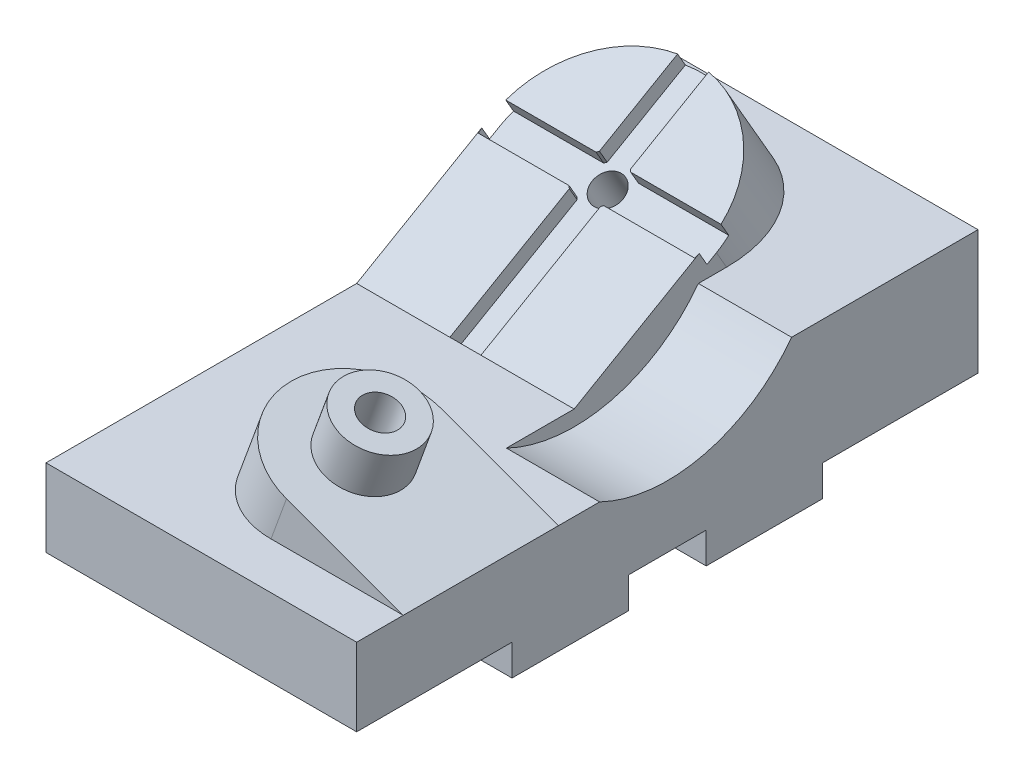
SolidWorks part; units mm, degrees
material "6061 Alloy"
ref_plane "Front Plane" through (0, 0, 0) normal (0, 0, 1) x (1, 0, 0)
ref_plane "Top Plane" through (0, 0, 0) normal (0, 1, 0) x (1, 0, 0)
ref_plane "Right Plane" through (0, 0, 0) normal (1, 0, 0) x (0, 0, -1)
sketch "Sketch1" plane through (0, 0, 0) normal (0, 1, 0) x (1, 0, 0)
  line L1 (0, 0) -> (100, 0)
  line L2 (0, 0) -> (0, -200)
  line L3 (0, -200) -> (100, -200)
  line L4 (100, 0) -> (100, -200)
  dimension "D1" = 100
  dimension "D2" = 200
extrude "Boss-Extrude1" add sketch "Sketch1" along normal blind 25
ref_plane "Plane1" through (19.7326, 54.2149, 0) normal (0.342, 0.9397, 0) x (0, 0, -1)
sketch "Sketch3" plane through (19.7326, 54.2149, 0) normal (0.342, 0.9397, 0) x (0, 0, -1)
  line L0 (-200, -85.4188) -> (0, -85.4188) construction
  line L1 (-185, -85.4188) -> (-135, -85.4188)
  line L2 (-185, -85.4188) -> (-185, -45.4188)
  line L4 (-135, -85.4188) -> (-135, -45.4188)
  arc A0 (-135, -45.4188) -> (-185, -45.4188) centre (-160, -45.4188) ccw
  dimension "D1" = 15
  dimension "D2" = 50
  dimension "D3" = 40
extrude "Boss-Extrude3" add sketch "Sketch3" against normal up to surface (26.6044 mm away)
sketch "Sketch4" plane through (19.7326, 54.2149, 0) normal (0.342, 0.9397, 0) x (0.9397, -0.342, 0)
  circle A0 centre (45.4188, -160) radius 12.5
  dimension "D1" = 25
extrude "Boss-Extrude4" add sketch "Sketch4" along normal blind 15
sketch "Sketch5" plane through (24.8629, 68.3103, 0) normal (0.342, 0.9397, 0) x (0.9397, -0.342, 0)
  circle A0 centre (45.4188, -160) radius 6
  dimension "D1" = 12
extrude "Cut-Extrude1" cut sketch "Sketch5" against normal through all
sketch "Sketch6" plane through (0, 0, 0) normal (0, -1, 0) x (1, 0, 0)
  line L0 (100, 200) -> (100, 0) construction
  line L1 (100, 150) -> (0, 150)
  line L2 (100, 150) -> (100, 112.5)
  line L3 (100, 112.5) -> (0, 112.5)
  line L4 (0, 150) -> (0, 112.5)
  line L5 (0, 0) -> (0, 200) construction
  line L6 (0, 200) -> (100, 200) construction
  dimension "D1" = 50
  dimension "D2" = 37.5
extrude "Boss-Extrude5" add sketch "Sketch6" along normal blind 10
sketch "Sketch7" plane through (0, 0, 0) normal (0, -1, 0) x (1, 0, 0)
  line L0 (100, 112.5) -> (100, 0) construction
  line L1 (100, 87.5) -> (0, 87.5)
  line L2 (100, 87.5) -> (100, 50)
  line L3 (100, 50) -> (0, 50)
  line L4 (0, 87.5) -> (0, 50)
  line L5 (0, 0) -> (0, 112.5) construction
  line L6 (0, 112.5) -> (100, 112.5) construction
  line L7 (100, 150) -> (0, 150) construction
  dimension "D1" = 25
  dimension "D2" = 100
extrude "Boss-Extrude6" add sketch "Sketch7" along normal blind 10
sketch "Sketch8" plane through (0, 25, 0) normal (0, 1, 0) x (1, 0, 0)
  line L0 (0, 0) -> (0, -200) construction
  line L1 (100, 0) -> (0, 0)
  line L2 (100, 0) -> (100, -60)
  line L3 (100, -60) -> (0, -60)
  line L4 (0, 0) -> (0, -60)
  dimension "D1" = 60
extrude "Boss-Extrude7" add sketch "Sketch8" along normal blind 15
sketch "Sketch9" plane through (0, 25, 0) normal (0, 1, 0) x (1, 0, 0)
  line L0 (0, -100) -> (100, -100) construction
  line L1 (0, -60) -> (0, -200) construction
  line L2 (100, -135) -> (100, -60) construction
  line L3 (0, -200) -> (100, -200) construction
  dimension "D1" = 100
ref_plane "Plane2" through (0, 62.0513, 35.8253) normal (0, 0.866, 0.5) x (1, 0, 0)
sketch "Sketch10" plane through (0, 62.0513, 35.8253) normal (0, 0.866, 0.5) x (1, 0, 0)
  line L0 (0, -74.1025) -> (70, -74.1025)
  line L1 (0, -74.1025) -> (100, -74.1025) construction
  line L2 (0, -74.1025) -> (0, -24.1025)
  line L3 (0, 20) -> (0, -31.9615) construction
  line L4 (70, -74.1025) -> (70, -24.1025)
  arc A0 (70, -24.1025) -> (0, -24.1025) centre (35, -24.1025) ccw
  dimension "D1" = 70
  dimension "D2" = 50
  dimension "D3" = 50
extrude "Boss-Extrude9" add sketch "Sketch10" against normal blind 37
sketch "Sketch12" plane through (0, 62.0513, 35.8253) normal (0, 0.866, 0.5) x (1, 0, 0)
  line L0 (35, 10.8975) -> (35, -74.0803) construction
  line L1 (0, -24.1025) -> (70, -24.1025) construction
  arc A0 (70, -24.1025) -> (0, -24.1025) centre (35, -24.1025) ccw construction
  circle A1 centre (35, -24.1025) radius 7.5
  dimension "D1" = 15
extrude "Cut-Extrude7" cut sketch "Sketch12" against normal blind 5
sketch "Sketch13" plane through (0, 62.0513, 35.8253) normal (0, 0.866, 0.5) x (1, 0, 0)
  line L0 (35, -31.4658) -> (35, -74.1025) construction
  line L1 (0, -74.1025) -> (100, -74.1025) construction
  line L2 (35, -74.1025) -> (40, -74.1025)
  line L3 (40, -74.1025) -> (40, -29.5079)
  line L4 (35, -74.1025) -> (30, -74.1025)
  line L5 (30, -74.1025) -> (30, -29.5079)
  line L6 (35, -16.7393) -> (35, 10.8975) construction
  line L8 (40, -18.6972) -> (40, 10.5385)
  line L9 (30, -18.6972) -> (30, 10.5385)
  arc A0 (40, -18.6972) -> (30, -18.6972) centre (35, -24.1025) ccw
  arc A1 (70, -24.1025) -> (0, -24.1025) centre (35, -24.1025) ccw construction
  arc A2 (40, 10.5385) -> (30, 10.5385) centre (35, -24.1025) ccw
  arc A4 (30, -29.5079) -> (40, -29.5079) centre (35, -24.1025) ccw
  dimension "D1" = 5
  dimension "D2" = 5
extrude "Cut-Extrude8" cut sketch "Sketch13" against normal blind 5
sketch "Sketch14" plane through (0, 62.0513, 35.8253) normal (0, 0.866, 0.5) x (1, 0, 0)
  line L0 (42.5, -24.1025) -> (70, -24.1025) construction
  line L1 (27.5, -24.1025) -> (-0.1762, -24.1025) construction
  line L2 (29.4098, -19.1025) -> (0.181, -19.1025)
  line L3 (0.181, -29.1025) -> (29.4098, -29.1025)
  line L4 (40.5902, -19.1025) -> (69.819, -19.1025)
  line L5 (40.5902, -29.1025) -> (69.819, -29.1025)
  arc A0 (29.4098, -19.1025) -> (29.4098, -29.1025) centre (35, -24.1025) ccw
  arc A1 (69.819, -29.1025) -> (69.819, -19.1025) centre (35, -24.1025) ccw
  arc A2 (0.181, -19.1025) -> (0.181, -29.1025) centre (35, -24.1025) ccw
  arc A3 (40.5902, -29.1025) -> (40.5902, -19.1025) centre (35, -24.1025) ccw
  dimension "D1" = 15
  dimension "D2" = 5
  dimension "D3" = 5
  dimension "D4" = 5
extrude "Cut-Extrude9" cut sketch "Sketch14" against normal blind 5
sketch "Sketch16" plane through (100, 0, 0) normal (1, 0, 0) x (0, 0, -1)
  line L0 (-60, 40) -> (-100, 70) construction
  line L1 (-100, 70) -> (-100, 20) construction
  line L2 (-100, 20) -> (-100, 25) construction
  line L3 (-135, 25) -> (-60, 25) construction
  line L4 (-121.7945, 25) -> (-200, 25)
  line L5 (-200, 25) -> (-200, 0)
  line L6 (-200, 0) -> (-150, 0) construction
  line L7 (-200, 0) -> (-150, 0)
  line L8 (-150, 0) -> (-150, -10)
  line L9 (-150, -10) -> (-112.5, -10)
  line L10 (-112.5, -10) -> (-112.5, 0)
  line L11 (-112.5, -10) -> (-112.5, 0) construction
  line L12 (-112.5, 0) -> (-87.5, 0)
  line L13 (-87.5, 0) -> (-87.5, -10)
  line L14 (-87.5, -10) -> (-50, -10)
  line L15 (-50, -10) -> (-50, 0)
  line L16 (-50, 0) -> (0, 0)
  line L17 (0, 0) -> (0, 40)
  line L18 (0, 40) -> (-60, 40)
  arc A0 (-60, 40) -> (-121.7945, 25) centre (-100, 70) cw
  dimension "D1" = 50
  dimension "D2" = 50
  dimension "D3" = 5
  dimension "D4" = 0
extrude "Boss-Extrude10" add sketch "Sketch16" against normal blind 30
sketch "Sketch17" plane through (100, 0, 0) normal (1, 0, 0) x (0, 0, -1)
  line L0 (-60, 40) -> (-100, 70) construction
  line L1 (-100, 70) -> (-100, 20) construction
  line L2 (-100, 20) -> (-100, 25) construction
  line L3 (-135, 25) -> (-78.2055, 25) construction
  line L4 (-121.7945, 25) -> (-78.2055, 25)
  arc A0 (-78.2055, 25) -> (-121.7945, 25) centre (-100, 70) cw
  dimension "D1" = 50
  dimension "D2" = 50
  dimension "D3" = 5
  dimension "D4" = 0
extrude "Cut-Extrude10" cut sketch "Sketch17" against normal blind 30
sketch "Sketch18" plane through (0, 57.7211, 33.3253) normal (0, 0.866, 0.5) x (1, 0, 0)
  line L0 (0, -24.1025) -> (70, -24.1025) construction
  line L1 (35, 10.8975) -> (35, -74.1025) construction
  line L2 (0, -74.1025) -> (100, -74.1025) construction
  arc A0 (40, 10.5385) -> (30, 10.5385) centre (35, -24.1025) ccw construction
  circle A1 centre (35, -24.1025) radius 5
  dimension "D1" = 10
extrude "Cut-Extrude11" cut sketch "Sketch18" against normal through all
